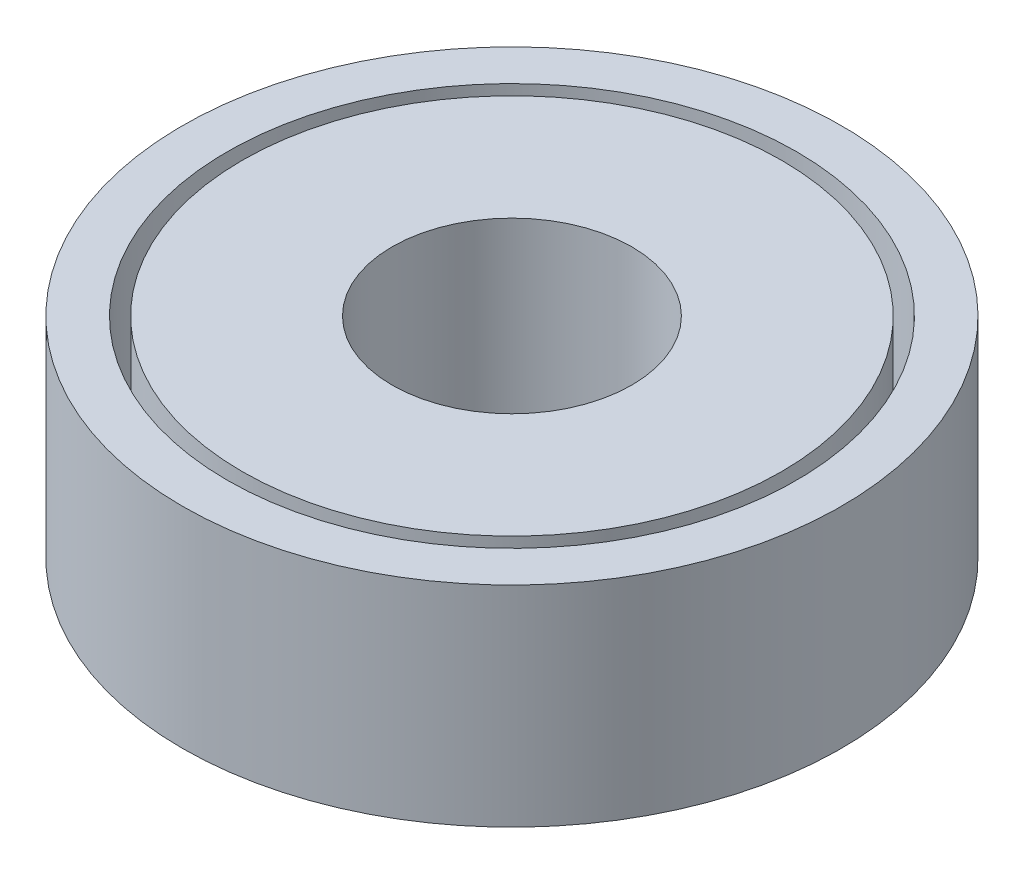
SolidWorks part; units mm, degrees
ref_plane "Front Plane" through (0, 0, 0) normal (0, 0, 1) x (1, 0, 0)
ref_plane "Top Plane" through (0, 0, 0) normal (0, 1, 0) x (1, 0, 0)
ref_plane "Right Plane" through (0, 0, 0) normal (1, 0, 0) x (0, 0, -1)
sketch "Sketch1" plane through (0, 0, 0) normal (0, 1, 0) x (1, 0, 0)
  circle A0 centre (0, 0) radius 11
  dimension "D1" = 22
extrude "Boss-Extrude1" add sketch "Sketch1" along normal blind 7
sketch "Sketch2" plane through (0, 7, 0) normal (0, 1, 0) x (1, 0, 0)
  circle A0 centre (0, 0) radius 9.5
  dimension "D1" = 19
extrude "Cut-Extrude1" cut sketch "Sketch2" against normal blind 7 contours A0
sketch "Sketch3" plane through (0, 0, 0) normal (0, 1, 0) x (1, 0, 0)
  circle A0 centre (0, 0) radius 9
  dimension "D1" = 18
extrude "Boss-Extrude2" add sketch "Sketch3" along normal blind 7
sketch "Sketch5" plane through (0, 0, 0) normal (0, -1, 0) x (1, 0, 0)
  circle A0 centre (0, 0) radius 4
  dimension "D1" = 8
extrude "Cut-Extrude2" cut sketch "Sketch5" against normal blind 7
